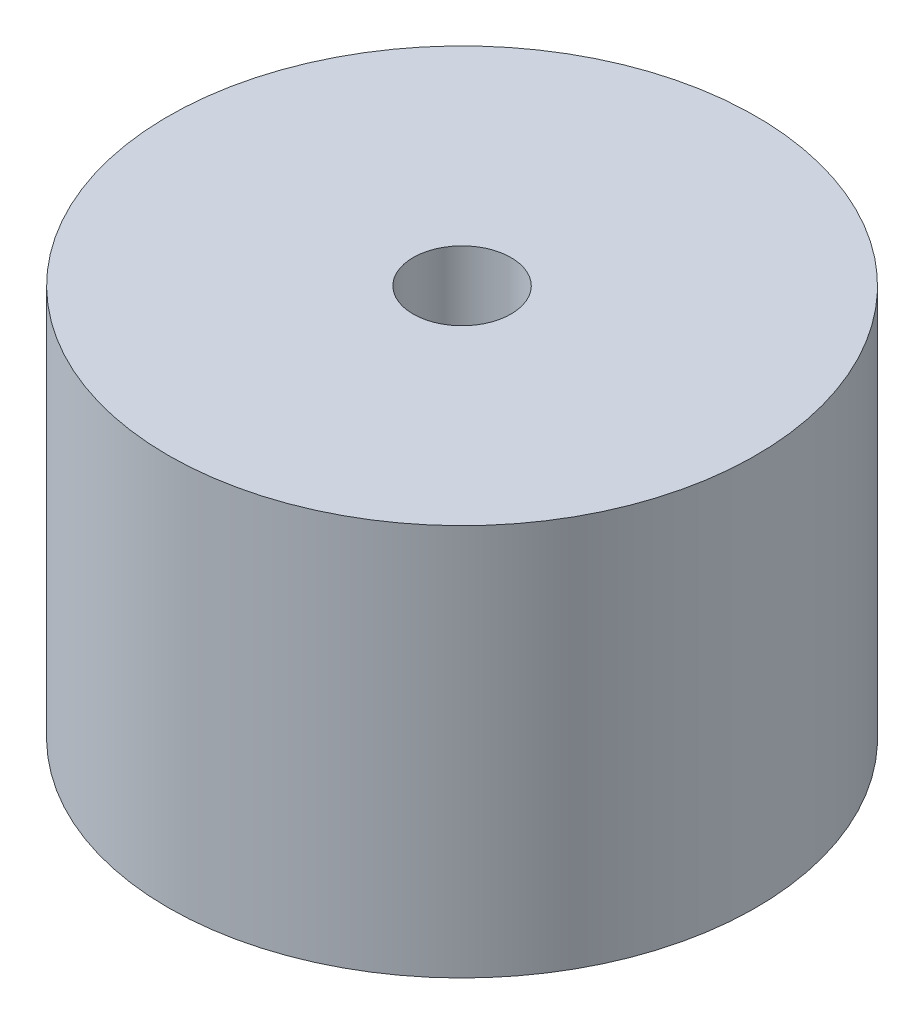
SolidWorks part; units mm, degrees
ref_plane "Front Plane" through (0, 0, 0) normal (0, 0, 1) x (1, 0, 0)
ref_plane "Top Plane" through (0, 0, 0) normal (0, 1, 0) x (1, 0, 0)
ref_plane "Right Plane" through (0, 0, 0) normal (1, 0, 0) x (0, 0, -1)
sketch "Sketch1" plane through (0, 0, 0) normal (0, 1, 0) x (1, 0, 0)
  circle A0 centre (0, 0) radius 9
  circle A1 centre (0, 0) radius 1.5
  dimension "D1" = 18
  dimension "D2" = 3
extrude "Boss-Extrude1" add sketch "Sketch1" along normal blind 12
